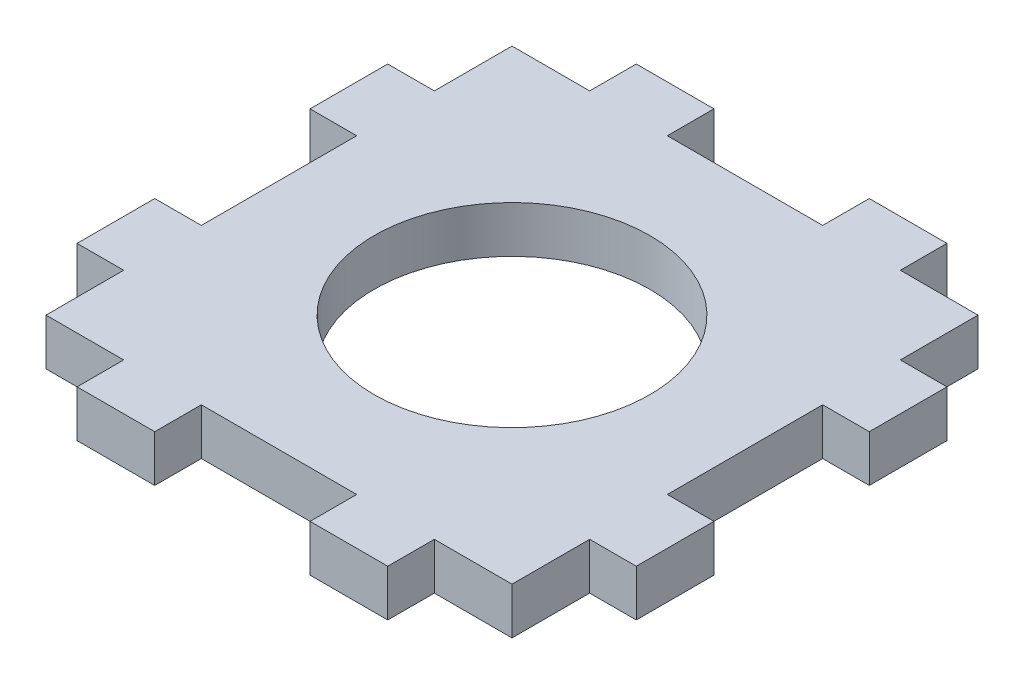
SolidWorks part; units mm, degrees
ref_plane "Front Plane" through (0, 0, 0) normal (0, 0, 1) x (1, 0, 0)
ref_plane "Top Plane" through (0, 0, 0) normal (0, 1, 0) x (1, 0, 0)
ref_plane "Right Plane" through (0, 0, 0) normal (1, 0, 0) x (0, 0, -1)
sketch "Sketch1" plane through (0, 0, 0) normal (0, 1, 0) x (1, 0, 0)
  line L0 (2.2355, 32.0745) -> (0, 30) construction
  line L1 (-30, 30) -> (30, 30)
  line L2 (-30, 30) -> (-30, -30)
  line L3 (-30, -30) -> (30, -30)
  line L4 (30, 30) -> (30, -30)
  line L5 (-30, 30) -> (30, -30) construction
  line L6 (-30, -30) -> (30, 30) construction
  line L7 (0, 30) -> (0, -30) construction
  line L8 (-30, 0) -> (30, 0) construction
  line L9 (10, -30) -> (10, -36)
  line L10 (-20, -30) -> (-10, -30)
  line L11 (-20, -30) -> (-20, -36)
  line L12 (-20, -36) -> (-10, -36)
  line L13 (-10, -30) -> (-10, -36)
  line L14 (20, -36) -> (10, -36)
  line L15 (20, -30) -> (20, -36)
  line L16 (20, -30) -> (10, -30)
  line L17 (-30, -10) -> (-36, -10)
  line L18 (-30, 20) -> (-30, 10)
  line L19 (-30, 20) -> (-36, 20)
  line L20 (-36, 20) -> (-36, 10)
  line L21 (-30, 10) -> (-36, 10)
  line L22 (-36, -20) -> (-36, -10)
  line L23 (-30, -20) -> (-36, -20)
  line L24 (-30, -20) -> (-30, -10)
  line L25 (-10, 30) -> (-10, 36)
  line L26 (20, 30) -> (10, 30)
  line L27 (20, 30) -> (20, 36)
  line L28 (20, 36) -> (10, 36)
  line L29 (10, 30) -> (10, 36)
  line L30 (-20, 36) -> (-10, 36)
  line L31 (-20, 30) -> (-20, 36)
  line L32 (-20, 30) -> (-10, 30)
  line L33 (30, 10) -> (36, 10)
  line L34 (30, -20) -> (30, -10)
  line L35 (30, -20) -> (36, -20)
  line L36 (36, -20) -> (36, -10)
  line L37 (30, -10) -> (36, -10)
  line L38 (36, 20) -> (36, 10)
  line L39 (30, 20) -> (36, 20)
  line L40 (30, 20) -> (30, 10)
  circle A0 centre (0, 0) radius 17.75
  point P0 (0, 0)
  point P46 (0, 0)
  dimension "D7" = 35.5
  dimension "D1" = 60
  dimension "D2" = 60
  dimension "D3" = 10
  dimension "D4" = 10
  dimension "D5" = 4
  dimension "D6" = 6
extrude "Boss-Extrude1" add sketch "Sketch1" along normal blind 6 contours L4 L1 L2 L3 | L15 L3 L9 L14 | L13 L3 L11 L12 | L37 L4 L35 L36 | L39 L4 L33 L38 | L23 L2 L17 L22 | L21 L2 L19 L20 | L31 L1 L25 L30 | L29 L1 L27 L28
